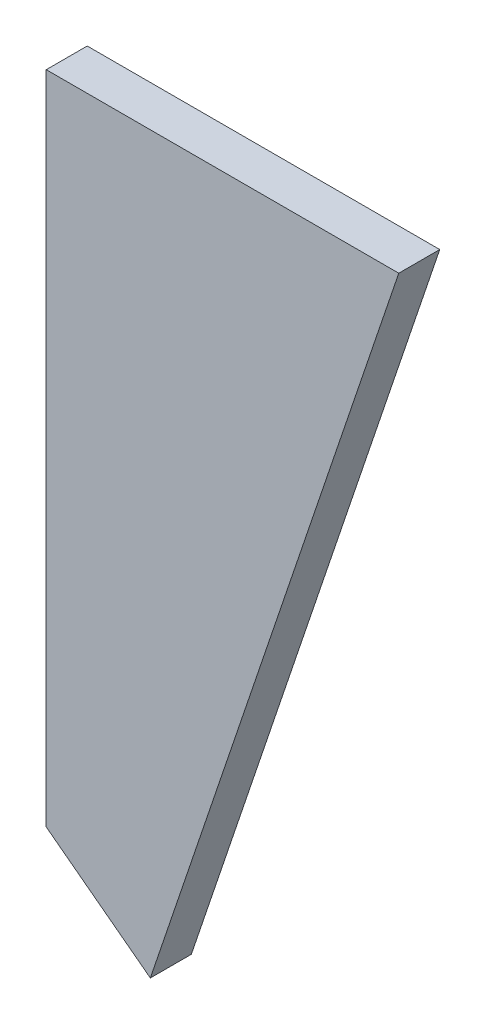
SolidWorks part; units mm, degrees
material "AISI 4340 Aço, normalizado"
ref_plane "Plano frontal" through (0, 0, 0) normal (0, 0, 1) x (1, 0, 0)
ref_plane "Plano superior" through (0, 0, 0) normal (0, 1, 0) x (1, 0, 0)
ref_plane "Plano direito" through (0, 0, 0) normal (1, 0, 0) x (0, 0, -1)
sketch "Esboço1" plane through (0, 0, 0) normal (0, 0, 1) x (1, 0, 0)
  line L1 (7.6181, -5.7626) -> (25.8, 48)
  line L2 (25.8, 48) -> (0, 48)
  line L3 (0, 48) -> (0, 0)
  line L5 (0, 0) -> (7.6181, -5.7626)
  dimension "D1" = 48
  dimension "D2" = 25.8
  dimension "D3" = 71.58
  dimension "D4" = 53.7626
extrude "Ressalto-extrusão1" add sketch "Esboço1" along normal blind 3
